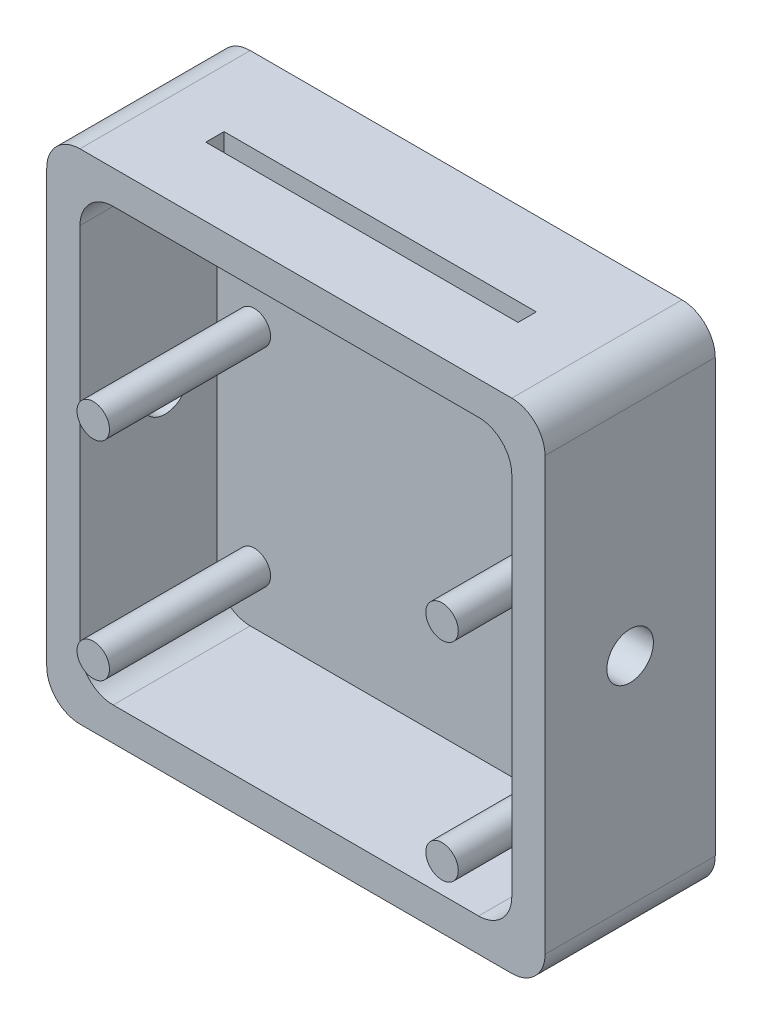
SolidWorks part; units mm, degrees
ref_plane "Front Plane" through (0, 0, 0) normal (0, 0, 1) x (1, 0, 0)
ref_plane "Top Plane" through (0, 0, 0) normal (0, 1, 0) x (1, 0, 0)
ref_plane "Right Plane" through (0, 0, 0) normal (1, 0, 0) x (0, 0, -1)
sketch "Sketch1" plane through (0, 0, 0) normal (0, 0, 1) x (1, 0, 0)
  line L1 (-20.4235, 15.2443) -> (9.5765, 15.2443)
  line L2 (-20.4235, 15.2443) -> (-20.4235, -14.7557)
  line L3 (-20.4235, -14.7557) -> (9.5765, -14.7557)
  line L4 (9.5765, 15.2443) -> (9.5765, -14.7557)
  dimension "D1" = 30
  dimension "D2" = 30
extrude "Boss-Extrude1" add sketch "Sketch1" along normal blind 2
sketch "Sketch4" plane through (0, 0, 2) normal (0, 0, 1) x (1, 0, 0)
  line L0 (-20.4235, 15.2443) -> (-20.4235, -14.7557) construction
  line L1 (-20.4235, -14.7557) -> (9.5765, -14.7557) construction
  line L2 (9.5765, -14.7557) -> (9.5765, 15.2443) construction
  circle A0 centre (-16.1735, 2.9433) radius 0.9775
  circle A1 centre (-16.1735, -9.5557) radius 0.9775
  circle A2 centre (4.8265, 2.9433) radius 0.9775
  circle A3 centre (4.8265, -9.5557) radius 0.9775
  dimension "D1" = 1.955
  dimension "D2" = 1.955
  dimension "D3" = 1.955
  dimension "D4" = 1.955
  dimension "D5" = 4.25
  dimension "D6" = 4.25
  dimension "D7" = 17.699
  dimension "D8" = 17.699
  dimension "D9" = 4.75
  dimension "D10" = 4.75
  dimension "D11" = 5.2
  dimension "D12" = 5.2
extrude "Boss-Extrude3" add sketch "Sketch4" along normal blind 9.7
sketch "Sketch5" plane through (0, 0, 2) normal (0, 0, 1) x (1, 0, 0)
  line L15 (7.5765, 13.2443) -> (-18.4235, 13.2443)
  line L20 (-18.4235, 13.2443) -> (-18.4235, -12.7557)
  line L21 (-18.4235, -12.7557) -> (7.5765, -12.7557)
  line L22 (7.5765, -12.7557) -> (7.5765, 13.2443)
  line L23 (-20.4235, 15.2443) -> (-20.4235, -14.7557)
  line L24 (-20.4235, -14.7557) -> (9.5765, -14.7557)
  line L25 (9.5765, -14.7557) -> (9.5765, 15.2443)
  line L26 (9.5765, 15.2443) -> (-20.4235, 15.2443)
  line L27 (-20.4235, 15.2443) -> (-20.4235, -14.7557)
  line L28 (-20.4235, -14.7557) -> (9.5765, -14.7557)
  line L29 (9.5765, -14.7557) -> (9.5765, 15.2443)
  line L30 (9.5765, 15.2443) -> (-20.4235, 15.2443)
  point P25 (0, 0)
  dimension "D1" = 0
  dimension "D2" = 2
extrude "Boss-Extrude4" add sketch "Sketch5" along normal blind 8.25
sketch "Sketch6" plane through (0, 15.2443, 0) normal (0, 1, 0) x (1, 0, 0)
  line L1 (-14.9822, -6.115) -> (3.8178, -6.115)
  line L2 (-14.9822, -6.115) -> (-14.9822, -5.015)
  line L3 (-14.9822, -5.015) -> (3.8178, -5.015)
  line L4 (3.8178, -6.115) -> (3.8178, -5.015)
  dimension "D1" = 18.8
  dimension "D2" = 1.1
extrude "Cut-Extrude1" cut sketch "Sketch6" against normal blind 10
fillet "Fillet1" radius 2 8 edges at (-20.4235, 15.2443, 5.125) (9.5765, 15.2443, 5.125) (7.5765, 13.2443, 6.125) (-18.4235, 13.2443, 6.125) (-18.4235, -12.7557, 6.125) (7.5765, -12.7557, 6.125) (9.5765, -14.7557, 5.125) (-20.4235, -14.7557, 5.125)
sketch "Sketch15" plane through (0, 0, 0) normal (0, 0, -1) x (-1, 0, 0)
  line L0 (-4.6787, 13.4807) -> (-4.6787, 10.5248) construction
  line L1 (-4.4887, 13.4807) -> (-4.4887, 10.5248)
  line L2 (-4.8687, 13.4807) -> (-4.8687, 10.5248)
  arc A0 (-4.4887, 13.4807) -> (-4.8687, 13.4807) centre (-4.6787, 13.4807) ccw
  arc A1 (-4.8687, 10.5248) -> (-4.4887, 10.5248) centre (-4.6787, 10.5248) ccw
  point P2 (-4.6787, 12.0028)
  dimension "D1" = 0.19
extrude "Cut-Extrude4" cut sketch "Sketch15" against normal blind 0.25
sketch "Sketch16" plane through (0, 0, 0) normal (0, 0, -1) x (-1, 0, 0)
  line L0 (-4.8687, 10.9233) -> (-4.7723, 10.9233)
  line L1 (-4.8687, 13.4807) -> (-4.8687, 10.5248) construction
  line L2 (-4.7723, 10.9233) -> (-4.7723, 13.4807)
  line L3 (-4.5988, 13.4807) -> (-4.5988, 10.9233)
  line L4 (-4.5988, 10.9233) -> (-4.4887, 10.9233)
  line L5 (-4.4887, 10.5248) -> (-4.4887, 13.4807) construction
  line L6 (-4.4887, 10.9233) -> (-4.4887, 13.4807)
  line L7 (-4.8687, 13.4807) -> (-4.8687, 10.9233)
  arc A0 (-4.7723, 13.4807) -> (-4.5988, 13.4807) centre (-4.6855, 13.4807) cw
  arc A1 (-4.4887, 13.4807) -> (-4.8687, 13.4807) centre (-4.6787, 13.4807) ccw
extrude "Boss-Extrude6" add sketch "Sketch16" against normal blind 0.05
sketch "Sketch19" plane through (0, 0, 0) normal (0, 0, -1) x (-1, 0, 0)
  line L0 (16.36, 10.8201) -> (16.4564, 10.8201)
  line L1 (16.4564, 10.8201) -> (16.4564, 13.3775)
  line L2 (16.6299, 13.3775) -> (16.6299, 10.8201)
  line L3 (16.6299, 10.8201) -> (16.74, 10.8201)
  line L4 (16.74, 10.8201) -> (16.74, 13.3775)
  line L5 (16.36, 13.3775) -> (16.36, 10.8201)
  line L6 (-4.6855, 13.5675) -> (19.8851, 13.5675) construction
  arc A0 (16.4564, 13.3775) -> (16.6299, 13.3775) centre (16.5431, 13.3775) cw
  arc A1 (16.74, 13.3775) -> (16.36, 13.3775) centre (16.55, 13.3775) ccw
  arc A3 (-4.5988, 13.4807) -> (-4.7723, 13.4807) centre (-4.6855, 13.4807) ccw construction
  point P15 (16.55, 13.5675)
sketch "Sketch20" plane through (0, 0, 0) normal (0, 0, -1) x (-1, 0, 0)
  line L0 (16.55, 13.3775) -> (16.55, 10.5154) construction
  line L1 (16.74, 13.3775) -> (16.74, 10.5154)
  line L2 (16.36, 13.3775) -> (16.36, 10.5154)
  line L3 (16.74, 10.8201) -> (16.74, 13.3775) construction
  arc A0 (16.74, 13.3775) -> (16.36, 13.3775) centre (16.55, 13.3775) ccw
  arc A1 (16.36, 10.5154) -> (16.74, 10.5154) centre (16.55, 10.5154) ccw
  arc A2 (16.74, 13.3775) -> (16.36, 13.3775) centre (16.55, 13.3775) ccw construction
  point P2 (16.55, 11.9464)
  point P12 (16.55, 10.2165)
  point P13 (16.55, 10.4002)
  point P14 (16.55, 10.5538)
  point P15 (16.55, 10.5154)
extrude "Cut-Extrude5" cut sketch "Sketch20" against normal blind 0.25
extrude "Boss-Extrude7" add sketch "Sketch19" against normal blind 0.05
sketch "Sketch23" plane through (-20.4235, 0, 0) normal (-1, 0, 0) x (0, 0, 1)
  circle A0 centre (5.125, 0.2443) radius 1.4
  dimension "D1" = 2.8
sketch "Sketch24" plane through (9.5765, 0, 0) normal (1, 0, 0) x (0, 0, -1)
  circle A0 centre (-5.125, 0.2443) radius 1.4
  dimension "D1" = 2.8
extrude "Cut-Extrude6" cut sketch "Sketch23" against normal blind 3
extrude "Cut-Extrude7" cut sketch "Sketch24" against normal blind 3
